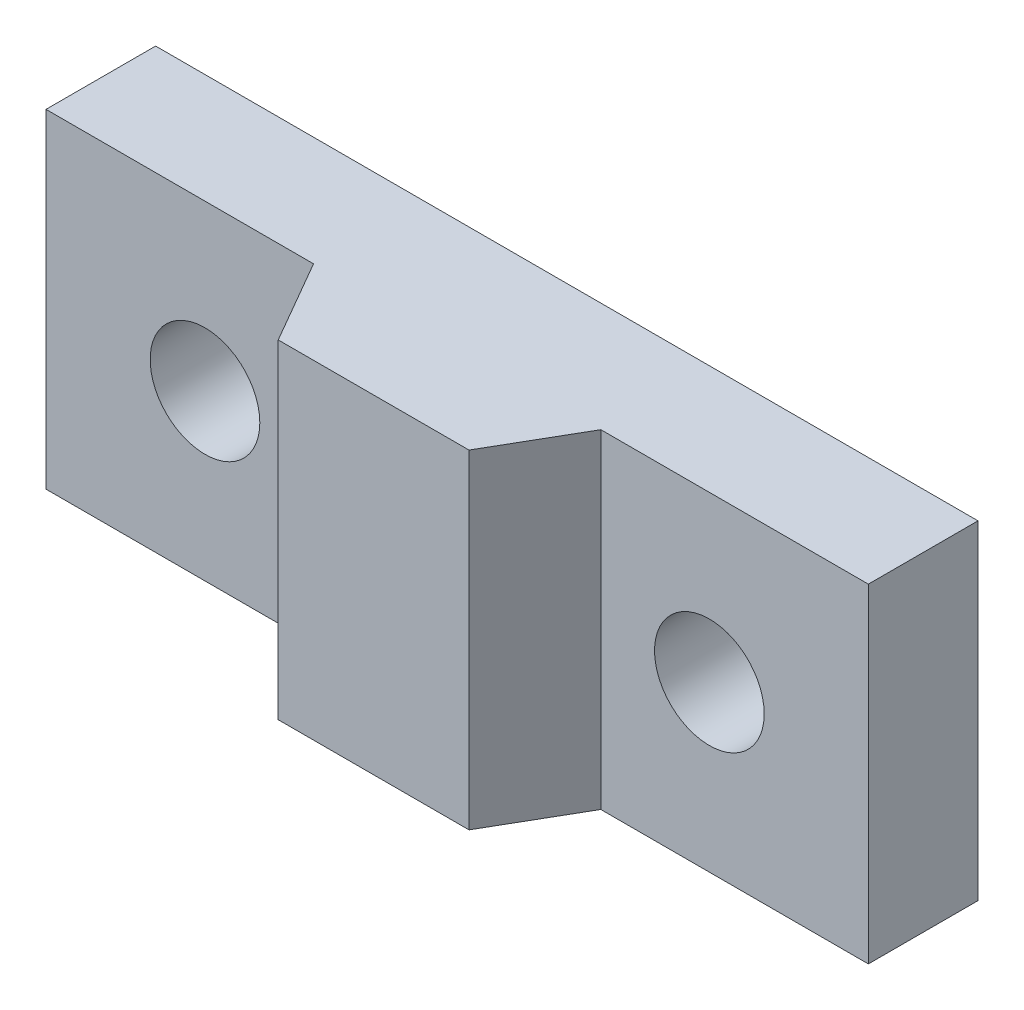
SolidWorks part; units mm, degrees
ref_plane "Front Plane" through (0, 0, 0) normal (0, 0, 1) x (1, 0, 0)
ref_plane "Top Plane" through (0, 0, 0) normal (0, 1, 0) x (1, 0, 0)
ref_plane "Right Plane" through (0, 0, 0) normal (1, 0, 0) x (0, 0, -1)
sketch "Sketch1" plane through (0, 0, 0) normal (0, 1, 0) x (1, 0, 0)
  line L0 (0, -1.27) -> (0, -10.0638)
  line L1 (-9.525, -1.27) -> (9.525, -1.27)
  line L2 (-9.525, -1.27) -> (-9.525, 1.27)
  line L3 (-9.525, 1.27) -> (9.525, 1.27)
  line L4 (9.525, -1.27) -> (9.525, 1.27)
  line L5 (-9.525, -1.27) -> (9.525, 1.27) construction
  line L6 (-9.525, 1.27) -> (9.525, -1.27) construction
  line L7 (-3.3274, 1.27) -> (3.3274, 1.27)
  line L8 (-3.3274, 1.27) -> (-3.3274, -1.27)
  line L9 (-3.3274, -1.27) -> (3.3274, -1.27)
  line L10 (3.3274, 1.27) -> (3.3274, -1.27)
  line L11 (-3.3274, 1.27) -> (3.3274, -1.27) construction
  line L12 (-3.3274, -1.27) -> (3.3274, 1.27) construction
  line L13 (-3.3274, -1.27) -> (0, -7.0332)
  line L14 (0, -7.0332) -> (3.3274, -1.27)
  line L15 (-3.3274, -1.27) -> (3.3274, -1.27)
  line L16 (-2.2098, -3.2057) -> (2.2098, -3.2057)
  point P0 (0, 0)
  point P6 (0, 0)
  dimension "D1" = 19.05
  dimension "D2" = 2.54
  dimension "D3" = 6.6548
  dimension "D5" = 4.4196
extrude "Boss-Extrude1" add sketch "Sketch1" along normal blind 7.62 contours L13 L16 L0 L1 | L0 L16 L14 L1 | L3 L10 L1 L4 | L10 L3 L8 L1 | L8 L3 L2 L1
sketch "Sketch3" plane through (0, 0, 3.2057) normal (0, 0, 1) x (1, 0, 0)
  line L0 (0, 7.62) -> (0, 0)
  line L1 (-2.2098, 7.62) -> (2.2098, 7.62) construction
  line L2 (0, 3.81) -> (-5.842, 3.81)
  circle A0 centre (-5.842, 3.81) radius 1.27
extrude "Cut-Extrude2" cut sketch "Sketch3" against normal up to next contours A0
mirror "Mirror2" about plane through (0, 0, 0) normal (1, 0, 0) of "Cut-Extrude2"
